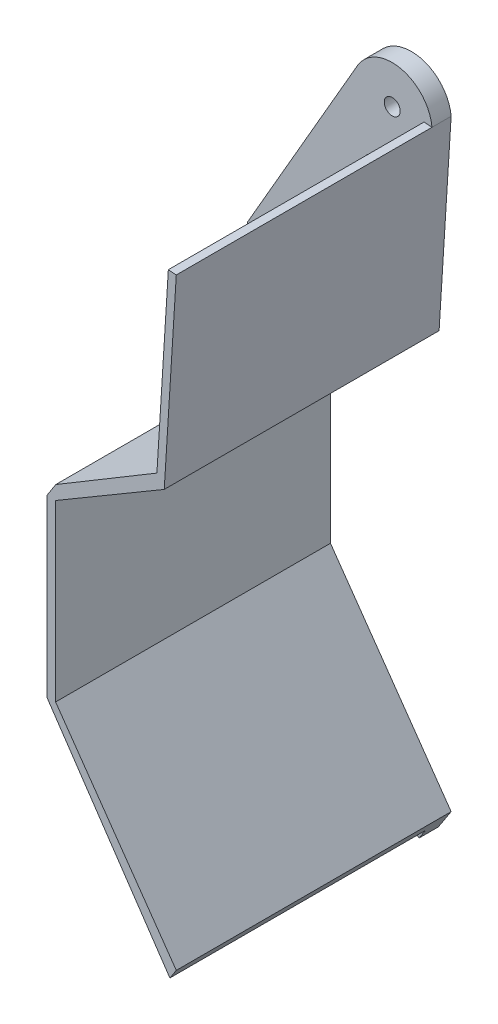
SolidWorks part; units mm, degrees
ref_plane "前视基准面" through (0, 0, 0) normal (0, 0, 1) x (1, 0, 0)
ref_plane "上视基准面" through (0, 0, 0) normal (0, 1, 0) x (1, 0, 0)
ref_plane "右视基准面" through (0, 0, 0) normal (1, 0, 0) x (0, 0, -1)
sketch "草图1" plane through (0, 0, 0) normal (0, 0, 1) x (1, 0, 0)
  line L0 (0.4413, 66.8945) -> (-16.8792, 36.8945)
  line L1 (-16.8792, 36.8945) -> (-16.8792, -3.1055)
  line L2 (-16.8792, -3.1055) -> (-5.3322, -23.1055)
  line L5 (-7.0008, 37.5151) -> (-6.8792, 37.579)
  line L26 (-5.3322, -23.1055) -> (9.9927, -33.1055)
  line L27 (11.9998, 64.1907) -> (10.1143, 34.1907)
  line L28 (10.1143, 34.1907) -> (-6.8792, 24.1907)
  line L29 (-6.8792, 24.1907) -> (-6.8792, 14.1907)
  line L32 (-6.8792, 14.1907) -> (-6.8792, -3.1055)
  line L35 (-6.8792, -3.1055) -> (11.9998, -30.0298)
  line L36 (11.9998, -30.0298) -> (9.9927, -33.1055)
  arc A4 (0.4413, 66.8945) -> (11.9998, 64.1907) centre (5.7669, 63.6033) cw
  dimension "D7" = 30
  dimension "D8" = 10
  dimension "D9" = 10
  dimension "D6" = 10
  dimension "D1" = 150
  dimension "D2" = 150
  dimension "D3" = 30
  dimension "D4" = 40
  dimension "D5" = 20
  dimension "D10" = 10
sketch "草图2" plane through (0, 0, 0) normal (0, 0, 1) x (1, 0, 0)
  circle A2 centre (5.7844, 63.8812) radius 1.25
  dimension "D1" = 2.5
extrude "凸台-拉伸4" add sketch "草图1" along normal blind 3
sketch "草图6" plane through (0, 0, 0) normal (0, 0, -1) x (-1, 0, 0)
  line L0 (6.8792, 24.1907) -> (8.2484, 24.1907)
  line L1 (8.2484, 24.1907) -> (8.2484, -3.1455)
  line L2 (8.2484, -3.1455) -> (-10.9962, -31.5677)
  line L3 (-11.9998, -30.0298) -> (-9.9927, -33.1055) construction
  line L13 (-11.9998, 64.1907) -> (-10.1143, 34.1907)
  line L14 (-10.1143, 34.1907) -> (6.8792, 24.1907)
  line L15 (6.8792, 24.1907) -> (6.8792, -3.1055)
  line L16 (6.8792, -3.1055) -> (-11.9998, -30.0298)
  line L17 (-11.9998, -30.0298) -> (-9.9927, -33.1055)
  line L18 (-9.9927, -33.1055) -> (5.3322, -23.1055)
  line L19 (5.3322, -23.1055) -> (16.8792, -3.1055)
  line L20 (16.8792, -3.1055) -> (16.8792, 36.8945)
  line L21 (16.8792, 36.8945) -> (-0.4413, 66.8945)
  line L24 (6.8792, 24.1907) -> (6.8792, -3.1055)
  line L25 (6.8792, -3.1055) -> (-11.9998, -30.0298)
  line L26 (-11.9998, -30.0298) -> (-10.9962, -31.5677)
  arc A1 (-0.4413, 66.8945) -> (-11.9998, 64.1907) centre (-5.7669, 63.6033) ccw
  dimension "D1" = 0
extrude "凸台-拉伸6" add sketch "草图6" against normal blind 43
sketch "草图9" plane through (0, 0, 3) normal (0, 0, 1) x (1, 0, 0)
  line L0 (-8.2484, 24.1907) -> (-6.8588, 26.3621)
  line L1 (-6.8588, 26.3621) -> (8.9665, 35.8285)
  line L2 (8.9665, 35.8285) -> (10.1143, 34.1907)
  line L13 (-8.2484, 24.1907) -> (-6.8792, 24.1907)
  line L14 (-6.8792, 24.1907) -> (10.1143, 34.1907)
  line L15 (10.1143, 34.1907) -> (11.9998, 64.1907)
  line L16 (0.4413, 66.8945) -> (-16.8792, 36.8945)
  line L17 (-16.8792, 36.8945) -> (-16.8792, -3.1055)
  line L18 (-16.8792, -3.1055) -> (-5.3322, -23.1055)
  line L19 (-5.3322, -23.1055) -> (9.9927, -33.1055)
  line L20 (9.9927, -33.1055) -> (10.9962, -31.5677)
  line L21 (10.9962, -31.5677) -> (-8.2484, -3.1455)
  line L22 (-8.2484, -3.1455) -> (-8.2484, 24.1907)
  line L23 (-8.2484, 24.1907) -> (-6.8792, 24.1907)
  line L24 (-6.8792, 24.1907) -> (10.1143, 34.1907)
  arc A1 (11.9998, 64.1907) -> (0.4413, 66.8945) centre (5.7669, 63.6033) ccw
  dimension "D1" = 2
  dimension "D2" = 0
extrude "凸台-拉伸7" add sketch "草图9" along normal blind 40
sketch "草图11" plane through (0, 0, 3) normal (0, 0, 1) x (1, 0, 0)
  line L0 (8.9665, 35.8285) -> (10.7561, 64.2811)
  line L1 (10.7561, 64.2811) -> (11.9998, 64.1907)
  line L13 (-6.8588, 26.3621) -> (8.9665, 35.8285)
  line L14 (8.9665, 35.8285) -> (10.1143, 34.1907)
  line L15 (10.1143, 34.1907) -> (11.9998, 64.1907)
  line L16 (0.4413, 66.8945) -> (-16.8792, 36.8945)
  line L17 (-16.8792, 36.8945) -> (-16.8792, -3.1055)
  line L18 (-16.8792, -3.1055) -> (-5.3322, -23.1055)
  line L19 (-5.3322, -23.1055) -> (9.9927, -33.1055)
  line L20 (9.9927, -33.1055) -> (10.9962, -31.5677)
  line L21 (10.9962, -31.5677) -> (-8.2484, -3.1455)
  line L22 (-8.2484, -3.1455) -> (-8.2484, 24.1907)
  line L23 (-8.2484, 24.1907) -> (-6.8588, 26.3621)
  line L25 (8.9665, 35.8285) -> (10.1143, 34.1907)
  line L26 (10.1143, 34.1907) -> (11.9998, 64.1907)
  arc A1 (11.9998, 64.1907) -> (0.4413, 66.8945) centre (5.7669, 63.6033) ccw
  dimension "D1" = 0
extrude "凸台-拉伸8" add sketch "草图11" along normal blind 40
sketch "草图14" plane through (0, 0, 0) normal (0, 0, -1) x (-1, 0, 0)
  circle A0 centre (-2.5917, 54.4046) radius 1.25
  circle A1 centre (-5.7844, 63.8812) radius 1.25
  point P5 (0, 0)
  dimension "D1" = 10
extrude "切除-拉伸3" cut sketch "草图14" against normal blind 10
equation "\"13mm.\"=10"
